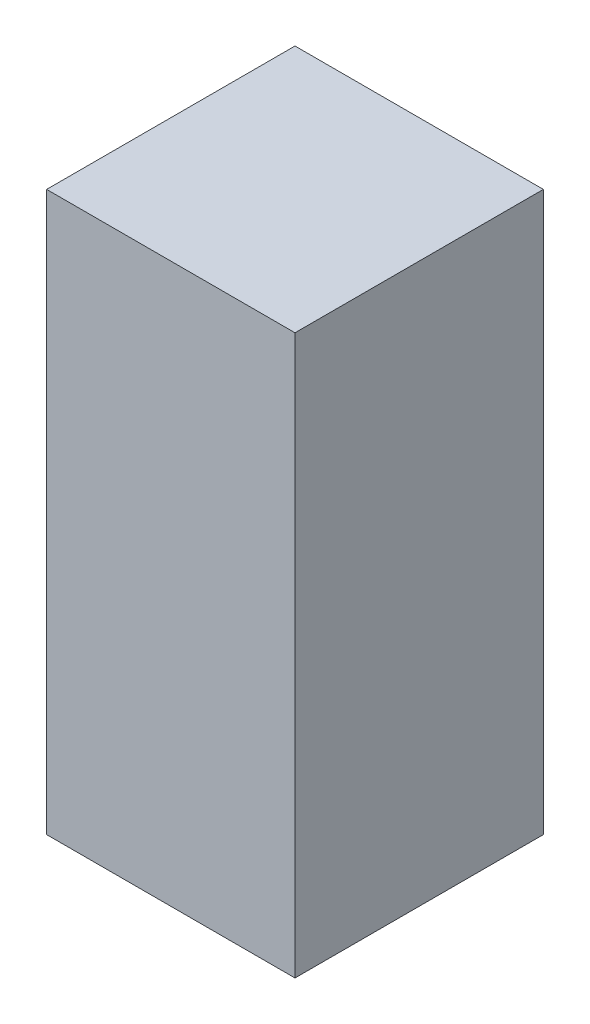
SolidWorks part; units mm, degrees
ref_plane "Front Plane" through (0, 0, 0) normal (0, 0, 1) x (1, 0, 0)
ref_plane "Top Plane" through (0, 0, 0) normal (0, 1, 0) x (1, 0, 0)
ref_plane "Right Plane" through (0, 0, 0) normal (1, 0, 0) x (0, 0, -1)
other "Configuration Table"
sketch "Sketch1" plane through (0, 0, 0) normal (0, 0, 1) x (1, 0, 0)
  line L1 (177.5, 552) -> (197.5, 552)
  line L2 (177.5, 552) -> (177.5, 597)
  line L3 (177.5, 597) -> (197.5, 597)
  line L4 (197.5, 552) -> (197.5, 597)
extrude "PACK_kose_plowu_3_1" add sketch "Sketch1" against normal blind 20 from offset 227.5 separate body
